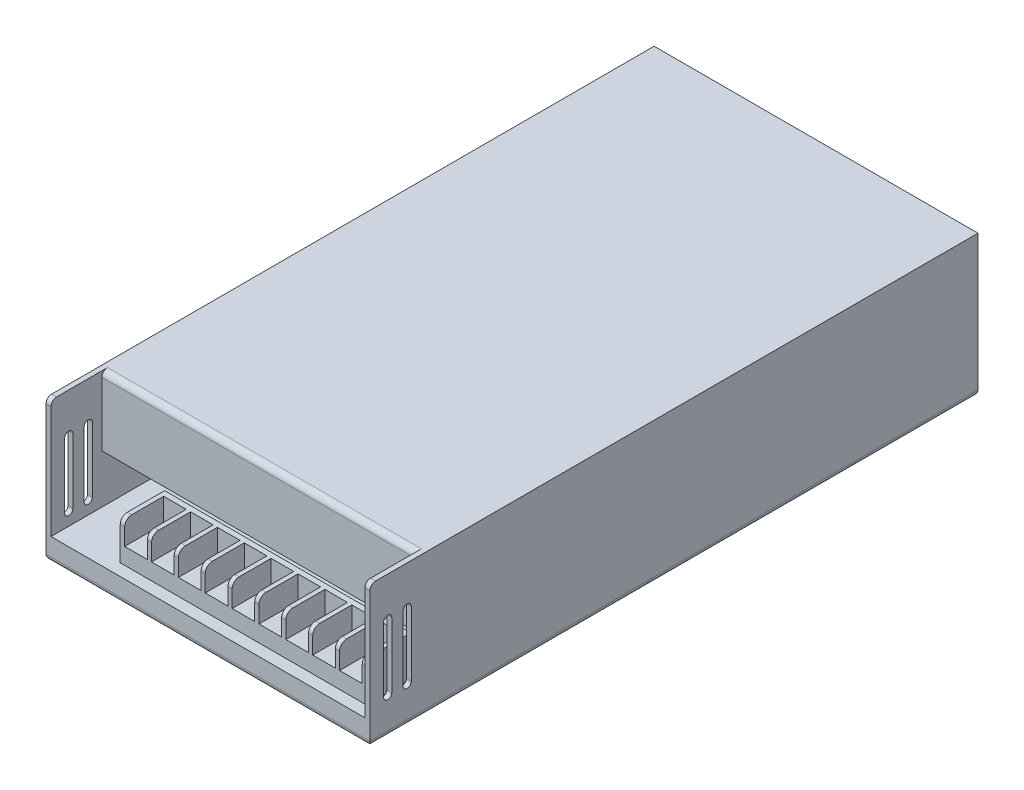
SolidWorks part; units mm, degrees
material "2024 Alloy"
ref_plane "Front Plane" through (0, 0, 0) normal (0, 0, 1) x (1, 0, 0)
ref_plane "Top Plane" through (0, 0, 0) normal (0, 1, 0) x (1, 0, 0)
ref_plane "Right Plane" through (0, 0, 0) normal (1, 0, 0) x (0, 0, -1)
sketch "Sketch1" plane through (0, 0, 0) normal (0, 1, 0) x (1, 0, 0)
  line L0 (0, 197) -> (0, -18) construction
  line L1 (-57.25, -18) -> (57.25, -18)
  line L2 (-57.25, -18) -> (-57.25, 197)
  line L3 (-57.25, 197) -> (57.25, 197)
  line L4 (57.25, -18) -> (57.25, 197)
  line L5 (-57.25, 0) -> (57.25, 0) construction
  dimension "D1" = 215
  dimension "D2" = 18
  dimension "D3" = 114.5
extrude "Boss-Extrude1" add sketch "Sketch1" along normal blind 41.75 and the other way blind 8.25
sketch "Sketch2" plane through (0, 0, 18) normal (0, 0, 1) x (1, 0, 0)
  line L0 (-57.25, 41.75) -> (57.25, 41.75) construction
  line L1 (-55.5, 0) -> (55.5, 0)
  line L2 (-55.5, 0) -> (-55.5, 41.75)
  line L3 (-55.5, 41.75) -> (55.5, 41.75)
  line L4 (55.5, 0) -> (55.5, 41.75)
  line L5 (0, 0) -> (0, 41.75) construction
  line L6 (57.25, -8.25) -> (57.25, 41.75) construction
  dimension "D1" = 1.75
extrude "Cut-Extrude1" cut sketch "Sketch2" against normal blind 18
sketch "Sketch3" plane through (57.25, 0, 0) normal (1, 0, 0) x (0, 0, -1)
  line L0 (-11.71, 27.7) -> (-11.71, 4.7) construction
  line L1 (-10.26, 27.7) -> (-10.26, 4.7)
  line L2 (-13.16, 27.7) -> (-13.16, 4.7)
  line L3 (-4.81, 27.7) -> (-4.81, 4.7) construction
  line L4 (-3.36, 27.7) -> (-3.36, 4.7)
  line L5 (-6.26, 27.7) -> (-6.26, 4.7)
  line L6 (-11.71, 16.2) -> (-4.81, 16.2) construction
  line L7 (-18, -8.25) -> (-18, 41.75) construction
  line L8 (-11.71, 29.15) -> (-11.71, 41.75) construction
  line L9 (-18, 41.75) -> (197, 41.75) construction
  line L10 (-11.71, 3.25) -> (-11.71, -8.25) construction
  line L11 (-18, -8.25) -> (197, -8.25) construction
  arc A0 (-10.26, 27.7) -> (-13.16, 27.7) centre (-11.71, 27.7) ccw
  arc A1 (-13.16, 4.7) -> (-10.26, 4.7) centre (-11.71, 4.7) ccw
  arc A2 (-3.36, 27.7) -> (-6.26, 27.7) centre (-4.81, 27.7) ccw
  arc A3 (-6.26, 4.7) -> (-3.36, 4.7) centre (-4.81, 4.7) ccw
  point P2 (-11.71, 16.2)
  point P7 (-4.81, 16.2)
  dimension "D1" = 4.84
  dimension "D2" = 2.9
  dimension "D3" = 4
  dimension "D4" = 12.6
  dimension "D5" = 11.5
extrude "Cut-Extrude2" cut sketch "Sketch3" against normal through all
fillet "Fillet1" radius 2 7 edges at (0, -8.25, -197) (-57.25, -8.25, -89.5) (0, -8.25, 18) (57.25, -8.25, -89.5) (0, 41.75, 0) (56.375, 41.75, 18) (-56.375, 41.75, 18)
sketch "Sketch4" plane through (0, 0, 0) normal (0, 1, 0) x (-1, 0, 0)
  line L0 (55.5, 0) -> (-55.5, 0) construction
  line L1 (35.2, 0) -> (-51.85, 0)
  line L2 (35.2, 0) -> (35.2, 13.8)
  line L3 (35.2, 13.8) -> (-51.85, 13.8)
  line L4 (-51.85, 0) -> (-51.85, 13.8)
  line L5 (55.5, 18) -> (-55.5, 18) construction
  line L6 (-55.5, 0) -> (-55.5, 18) construction
  line L7 (55.5, 0) -> (55.5, 18) construction
  dimension "D1" = 4.2
  dimension "D2" = 3.65
  dimension "D3" = 20.3
extrude "Boss-Extrude2" add sketch "Sketch4" along normal blind 14.25 separate body
sketch "Sketch7" plane through (0, 0, 0) normal (0, 0, 1) x (1, 0, 0)
  line L0 (-55.5, 39.75) -> (-55.5, 0) construction
  line L1 (-55.5, 17.25) -> (55.5, 17.25)
  line L2 (-55.5, 17.25) -> (-55.5, 0)
  line L3 (-55.5, 0) -> (55.5, 0)
  line L4 (55.5, 17.25) -> (55.5, 0)
  line L5 (-55.5, 0) -> (55.5, 0) construction
  line L6 (51.85, 14.25) -> (-35.2, 14.25) construction
  line L7 (55.5, 0) -> (55.5, 39.75) construction
  dimension "D1" = 3
extrude "Cut-Extrude4" cut sketch "Sketch7" against normal offset from surface (195.25 mm away) 1.75 up to face at (0, 17.75, -197)
fillet "Fillet2" radius 2.5 1 edges at (8.325, 14.25, 13.8)
sketch "Sketch6" plane through (0, 0, 13.8) normal (0, 0, 1) x (1, 0, 0)
  line L0 (-35.2, 14.25) -> (51.85, 14.25) construction
  line L1 (42.35, 14.25) -> (50.35, 14.25)
  line L2 (42.35, 14.25) -> (42.35, 5.8)
  line L3 (42.35, 5.8) -> (50.35, 5.8)
  line L4 (50.35, 14.25) -> (50.35, 5.8)
  line L6 (51.85, 11.75) -> (51.85, 0) construction
  line L7 (-35.2, 0) -> (51.85, 0) construction
  dimension "D1" = 5.8
  dimension "D2" = 1.5
  dimension "D3" = 8
extrude "Cut-Extrude3" cut sketch "Sketch6" against normal up to surface (13.8 mm away)
sketch "Sketch9" plane through (0, 0, 0) normal (0, 0, -1) x (-1, 0, 0)
  line L0 (35.2, 14.25) -> (35.2, 0) construction
  line L1 (-51.85, 14.25) -> (35.2, 14.25)
  line L2 (-51.85, 14.25) -> (-51.85, 0.5)
  line L3 (-51.85, 0.5) -> (35.2, 0.5)
  line L4 (35.2, 14.25) -> (35.2, 0.5)
  line L5 (-51.85, 0) -> (35.2, 0) construction
  dimension "D1" = 0.5
extrude "Boss-Extrude6" add sketch "Sketch9" along normal blind 1.9
pattern_linear "LPattern1" count 9 spacing 9.5 along (-1, 0, 0) of "Cut-Extrude3"
